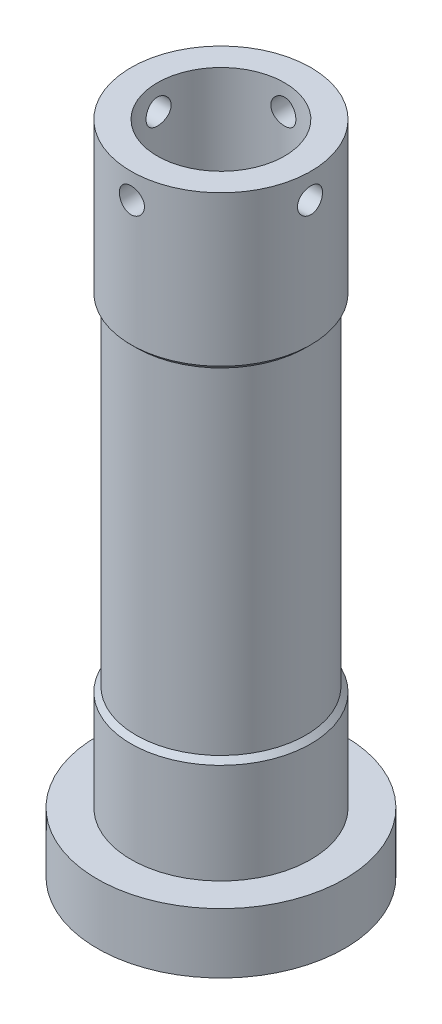
SolidWorks part; units mm, degrees
material "6061 合金"
ref_plane "前视基准面" through (0, 0, 0) normal (0, 0, 1) x (1, 0, 0)
ref_plane "上视基准面" through (0, 0, 0) normal (0, 1, 0) x (1, 0, 0)
ref_plane "右视基准面" through (0, 0, 0) normal (1, 0, 0) x (0, 0, -1)
other "Configuration Table"
sketch "草图1" plane through (0, 0, 0) normal (0, 0, 1) x (1, 0, 0)
  line L0 (6.35, 65.5) -> (6.35, 0)
  line L1 (6.35, 0) -> (12.35, 0)
  line L2 (12.35, 0) -> (12.35, 6)
  line L3 (12.35, 6) -> (8.975, 6)
  line L4 (8.475, 16.5) -> (8.475, 50)
  line L5 (8.475, 50) -> (8.975, 50.5)
  line L6 (8.975, 50.5) -> (8.975, 65.5)
  line L7 (8.975, 65.5) -> (6.35, 65.5)
  line L8 (0, 0) -> (0, 68.933) construction
  line L9 (8.475, 16.5) -> (8.975, 16)
  line L10 (8.975, 16) -> (8.975, 6)
  dimension "D1" = 17.95
  dimension "D2" = 65.5
  dimension "D3" = 15
  dimension "D4" = 12.7
  dimension "D5" = 45
  dimension "D6" = 0.5
  dimension "D7" = 6
  dimension "D8" = 45
  dimension "D9" = 10
  dimension "D10" = 6
revolve "旋转1" add sketch "草图1" angle 360 about L8
sketch "草图2" plane through (0, 65.5, 0) normal (0, 1, 0) x (1, 0, 0)
  line L0 (-7.4532, 5) -> (7.4532, 5)
  line L5 (-7.4532, -5) -> (7.4532, -5)
  line L6 (0, 0) -> (8.975, 0) construction
  circle A3 centre (0, 0) radius 8.975 construction
  circle A4 centre (0, 0) radius 8.975
  circle M5 centre (0, 0) radius 6.35
  circle M6 centre (0, 0) radius 8.975
  dimension "D1" = 5
extrude "切除-拉伸3" [suppressed] cut sketch "草图2" against normal blind 3 contours L0 M6 M5 | L5 M6 M5
sketch "草图4" plane through (0, 0, 0) normal (1, 0, 0) x (0, 0, -1)
  line L0 (0, 65.5) -> (0, 63) construction
  line L1 (6.35, 65.5) -> (-6.35, 65.5) construction
  dimension "D1" = 2.5
hole_wizard "M3 螺纹孔1" positions "草图5" profile "草图6" tap size "M3" standard "GB"
sketch "草图5" plane through (0, 0, 0) normal (1, 0, 0) x (0, 0, -1)
  point P0 (0, 63)
sketch "草图6" plane through (0, 63, 0) normal (0, 1, 0) x (0, 0, 1)
  line L0 (0, 0) -> (0, 12.35)
  line L1 (0, 12.35) -> (1.25, 12.35)
  line L2 (1.25, 12.35) -> (1.25, 0)
  line L5 (1.25, 0) -> (0, 0)
  line L11 (0, -6.35) -> (0, 107.95) construction
  dimension "通孔螺纹孔钻头直径" = 2.5
  dimension "通孔螺纹孔钻头深度" = 12.35
cosmetic thread "孔螺蚊线1" parameters "D2"=3
pattern_circular "阵列(圆周)1" count 4 over 360 about axis through (0, 65.5, 0) along (0, -1, 0) of "M3 螺纹孔1"
sketch "草图7" plane through (0, 65.5, 0) normal (0, 1, 0) x (1, 0, 0)
  line L0 (0, 6.35) -> (0, 8.975) construction
  circle A0 centre (0, 0) radius 6.35 construction
  circle A1 centre (0, 0) radius 8.975 construction
